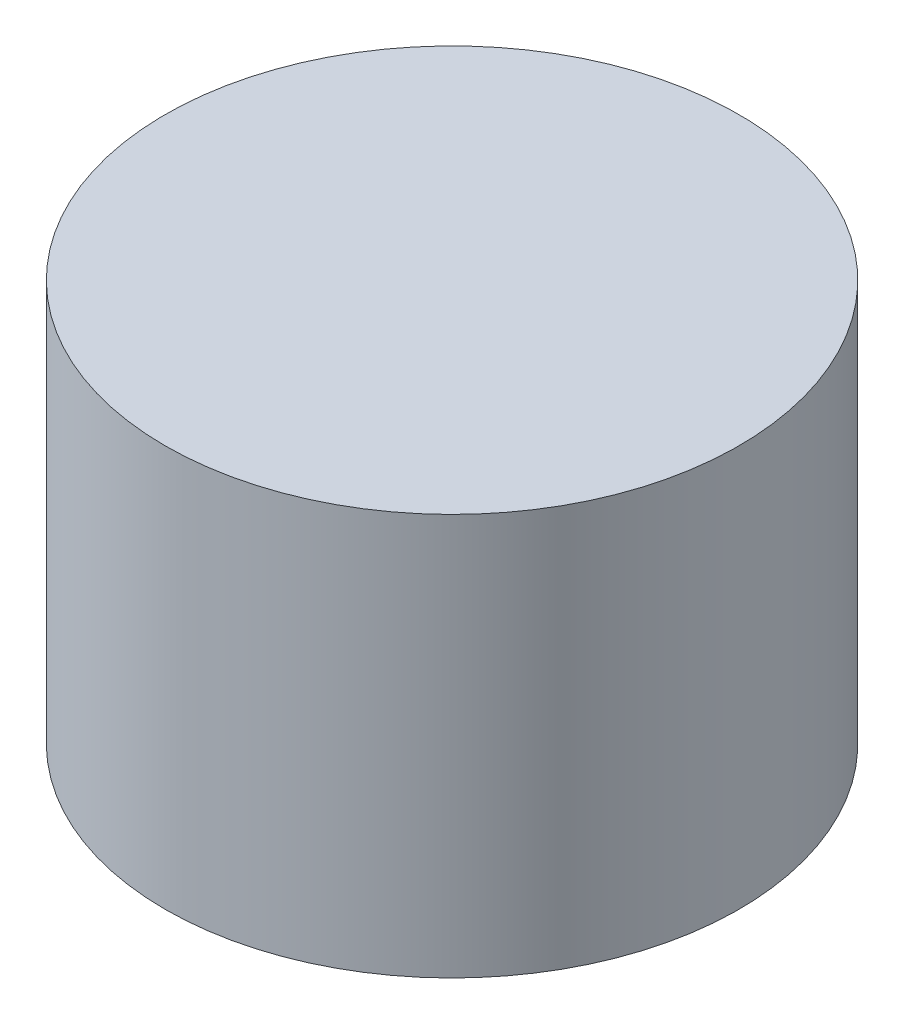
SolidWorks part; units mm, degrees
ref_plane "Front Plane" through (0, 0, 0) normal (0, 0, 1) x (1, 0, 0)
ref_plane "Top Plane" through (0, 0, 0) normal (0, 1, 0) x (1, 0, 0)
ref_plane "Right Plane" through (0, 0, 0) normal (1, 0, 0) x (0, 0, -1)
sketch "Sketch1" plane through (0, 0, 0) normal (0, 1, 0) x (1, 0, 0)
  line L0 (0, 27.8) -> (0, -27.8) construction
  line L1 (-27.8, 0) -> (27.8, 0) construction
  circle A0 centre (0, 0) radius 27.8
  dimension "D1" = 55.6
extrude "Boss-Extrude1" add sketch "Sketch1" along normal blind 38.9
